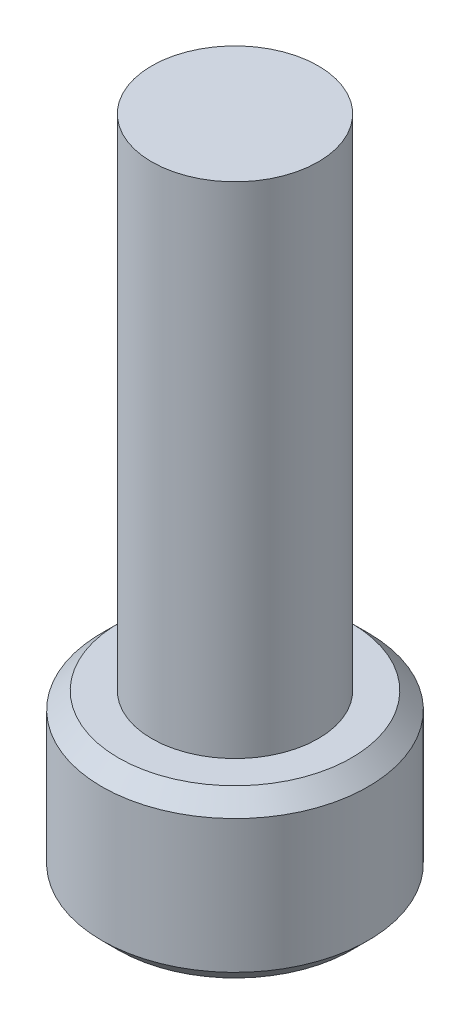
SolidWorks part; units mm, degrees
ref_plane "Front Plane" through (0, 0, 0) normal (0, 0, 1) x (1, 0, 0)
ref_plane "Top Plane" through (0, 0, 0) normal (0, 1, 0) x (1, 0, 0)
ref_plane "Right Plane" through (0, 0, 0) normal (1, 0, 0) x (0, 0, -1)
sketch "Sketch1" plane through (0, 0, 0) normal (0, 1, 0) x (1, 0, 0)
  circle A0 centre (0, 0) radius 2.5
extrude "Boss-Extrude1" add sketch "Sketch1" along normal blind 15
sketch "Sketch3" plane through (0, 0, 0) normal (0, 0, 1) x (1, 0, 0)
  line L0 (0, 0) -> (-4, 0)
  line L1 (-2.5, 0) -> (2.5, 0) construction
  line L2 (-4, 0) -> (-4, -5)
  line L3 (0, 0) -> (0, 12.6087) construction
  line L4 (-4, -5) -> (0, -5)
  line L5 (0, -5) -> (0, 0)
revolve "Revolve1" add sketch "Sketch3" angle 360 about L5
sketch "Sketch4" plane through (0, 0, 0) normal (0, 1, 0) x (1, 0, 0)
  line L1 (2.8868, 0) -> (1.4434, 2.5)
  line L2 (1.4434, 2.5) -> (-1.4434, 2.5)
  line L3 (-1.4434, 2.5) -> (-2.8868, 0)
  line L4 (-2.8868, 0) -> (-1.4434, -2.5)
  line L5 (-1.4434, -2.5) -> (1.4434, -2.5)
  line L6 (1.4434, -2.5) -> (2.8868, 0)
  circle A0 centre (0, 0) radius 2.5 construction
extrude "Cut-Extrude1" cut sketch "Sketch4" against normal blind 30 from offset 1 offset against normal yes
chamfer "Chamfer1" distance 0.5 angle 45 2 edges at (0, -5, -4) (0, 0, -4)
